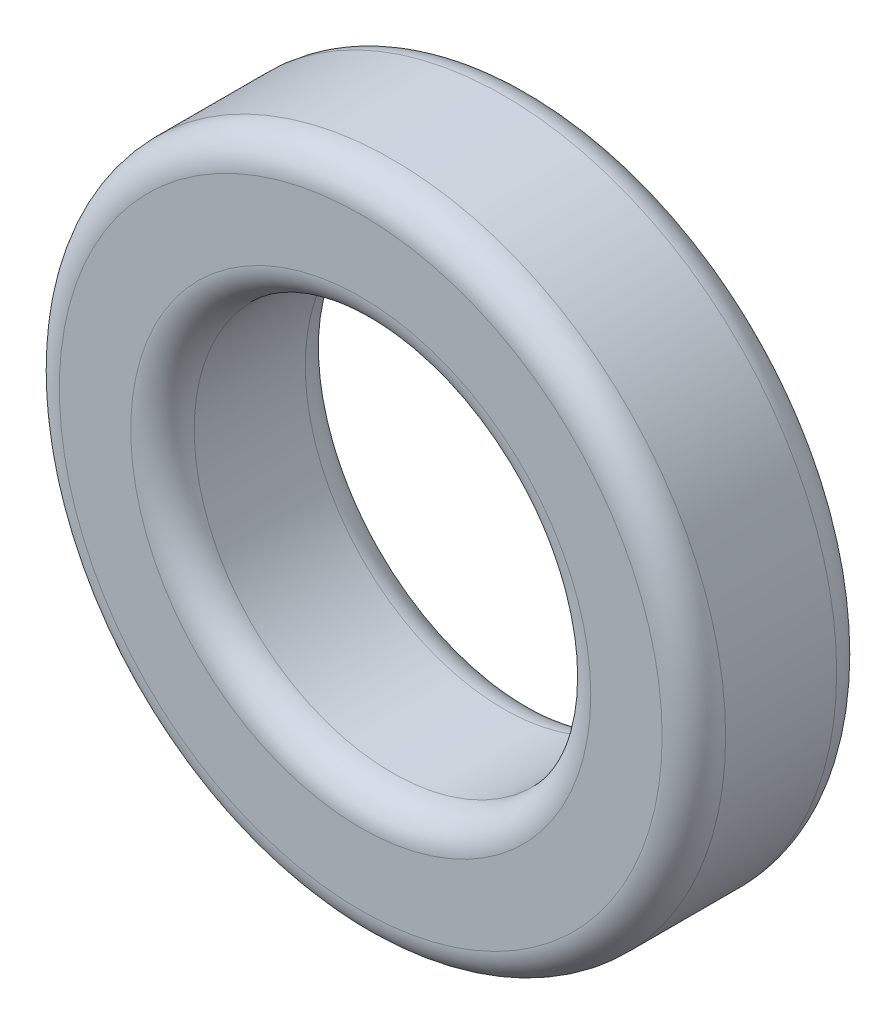
SolidWorks part; units mm, degrees
ref_plane "前视基准面" through (0, 0, 0) normal (0, 0, 1) x (1, 0, 0)
ref_plane "上视基准面" through (0, 0, 0) normal (0, 1, 0) x (1, 0, 0)
ref_plane "右视基准面" through (0, 0, 0) normal (1, 0, 0) x (0, 0, -1)
other "Configuration Table"
sketch "草图1" plane through (0, 0, 0) normal (0, 0, 1) x (1, 0, 0)
  circle A0 centre (0, 0) radius 21
  circle A1 centre (0, 0) radius 12.5
  dimension "D1" = 42
  dimension "D2" = 25
extrude "凸台-拉伸1" add sketch "草图1" along normal blind 11
fillet "圆角1" radius 2 4 edges at (12.5, 0, 0) (12.5, 0, 11) (21, 0, 0) (21, 0, 11)
